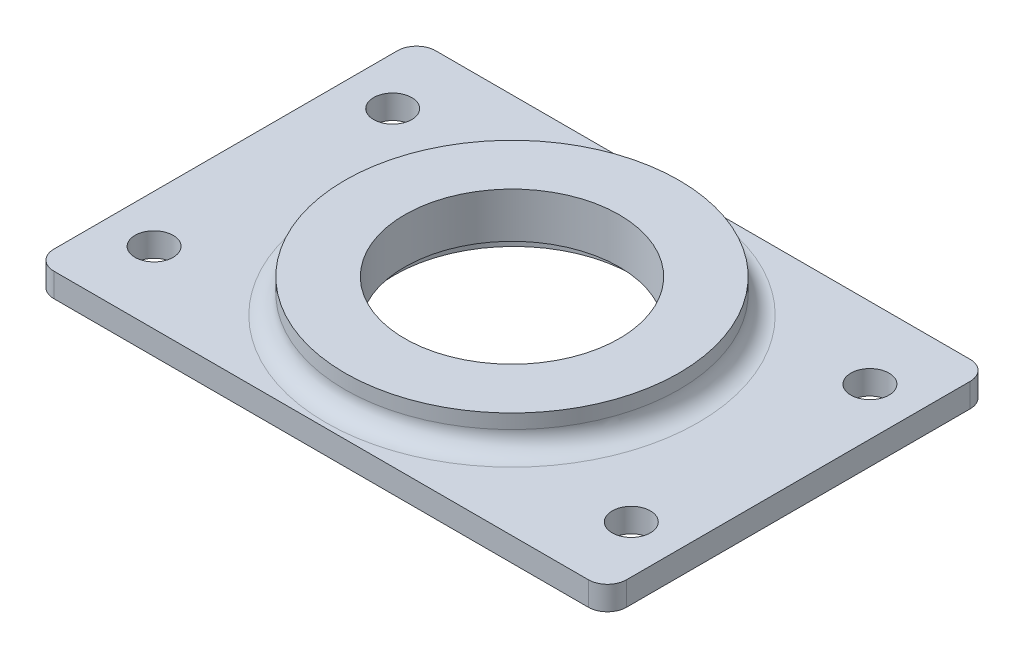
SolidWorks part; units mm, degrees
ref_plane "Front Plane" through (0, 0, 0) normal (0, 0, 1) x (1, 0, 0)
ref_plane "Top Plane" through (0, 0, 0) normal (0, 1, 0) x (1, 0, 0)
ref_plane "Right Plane" through (0, 0, 0) normal (1, 0, 0) x (0, 0, -1)
sketch "Sketch1" plane through (0, 0, 0) normal (0, 1, 0) x (1, 0, 0)
  line L1 (0, 0) -> (76.2, 0)
  line L2 (0, 0) -> (0, 50.8)
  line L3 (0, 50.8) -> (76.2, 50.8)
  line L4 (76.2, 0) -> (76.2, 50.8)
  circle A0 centre (38.1, 25.4) radius 14.2748
  dimension "D5" = 28.5496
  dimension "D1" = 50.8
  dimension "D2" = 76.2
  dimension "D3" = 38.1
  dimension "D4" = 25.4
extrude "Boss-Extrude1" add sketch "Sketch1" along normal blind 3.175
sketch "Sketch2" plane through (0, 3.175, 0) normal (0, 1, 0) x (1, 0, 0)
  circle A0 centre (38.1, 25.4) radius 22.225
  dimension "D1" = 44.45
extrude "Boss-Extrude2" add sketch "Sketch2" along normal blind 4.445
sketch "Sketch3" plane through (0, 3.175, 0) normal (0, -1, 0) x (1, 0, 0)
  circle A1 centre (38.1, -25.4) radius 14.2748
  circle A2 centre (38.1, -25.4) radius 14.2748
  dimension "D1" = 0
extrude "Cut-Extrude1" cut sketch "Sketch3" against normal through all
sketch "Sketch4" plane through (0, 0, 0) normal (0, -1, 0) x (-1, 0, 0)
  line L0 (0, 0) -> (-76.2, 0) construction
  circle A0 centre (-38.3325, 25.4) radius 15.8623
  dimension "D1" = 31.7246
  dimension "D2" = 25.4
extrude "Cut-Extrude2" cut sketch "Sketch4" against normal blind 1.6002
fillet "Fillet1" radius 2.54 1 edges at (38.1, 3.175, -47.625)
fillet "Fillet2" radius 2.54 4 edges at (0, 1.5875, -50.8) (76.2, 1.5875, -50.8) (0, 1.5875, 0) (76.2, 1.5875, 0)
sketch "Sketch5" plane through (0, 3.175, 0) normal (0, 1, 0) x (1, 0, 0)
  line L0 (73.66, 50.8) -> (2.54, 50.8) construction
  line L1 (0, 48.26) -> (0, 2.54) construction
  line L2 (2.54, 0) -> (73.66, 0) construction
  line L3 (76.2, 2.54) -> (76.2, 48.26) construction
  circle A0 centre (69.85, 41.275) radius 2.54
  circle A1 centre (69.85, 9.525) radius 2.54
  circle A2 centre (6.35, 9.525) radius 2.54
  circle A3 centre (6.35, 41.275) radius 2.54
  dimension "D9" = 5.08
  dimension "D10" = 5.08
  dimension "D11" = 5.08
  dimension "D12" = 5.08
  dimension "D1" = 9.525
  dimension "D2" = 6.35
  dimension "D3" = 6.35
  dimension "D4" = 9.525
  dimension "D5" = 9.525
  dimension "D6" = 6.35
  dimension "D7" = 9.525
  dimension "D8" = 6.35
extrude "Cut-Extrude3" cut sketch "Sketch5" against normal through all
